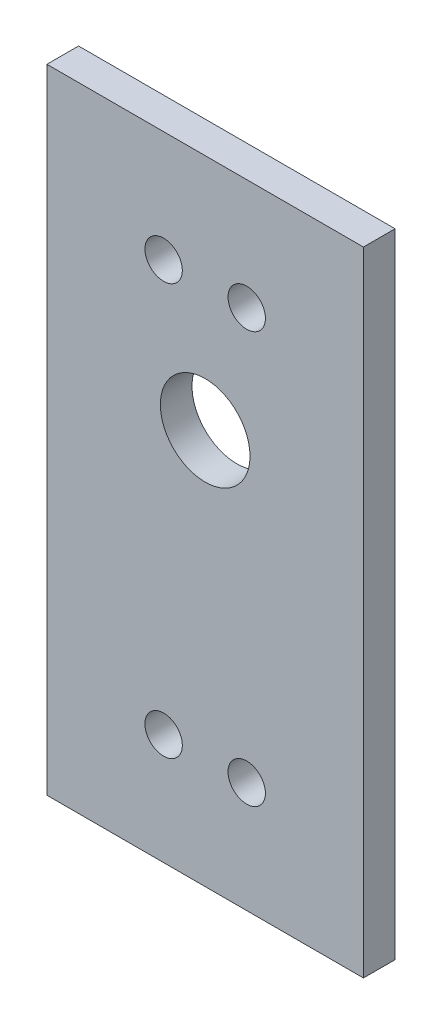
SolidWorks part; units mm, degrees
ref_plane "Front Plane" through (0, 0, 0) normal (0, 0, 1) x (1, 0, 0)
ref_plane "Top Plane" through (0, 0, 0) normal (0, 1, 0) x (1, 0, 0)
ref_plane "Right Plane" through (0, 0, 0) normal (1, 0, 0) x (0, 0, -1)
sketch "Sketch1" plane through (0, 0, 0) normal (0, 0, 1) x (1, 0, 0)
  line L1 (-19.05, 38.1) -> (19.05, 38.1)
  line L2 (-19.05, 38.1) -> (-19.05, -38.1)
  line L3 (-19.05, -38.1) -> (19.05, -38.1)
  line L4 (19.05, 38.1) -> (19.05, -38.1)
  line L5 (-19.05, 38.1) -> (19.05, -38.1) construction
  line L6 (-19.05, -38.1) -> (19.05, 38.1) construction
  point P0 (0, 0)
  dimension "D1" = 76.2
  dimension "D2" = 38.1
extrude "Boss-Extrude1" add sketch "Sketch1" along normal blind 3.81
sketch "Sketch2" plane through (0, 0, 3.81) normal (0, 0, 1) x (1, 0, 0)
  line L0 (0, 0) -> (0, -24.75) construction
  line L1 (-5, 24.75) -> (5, 24.75) construction
  line L2 (-5, 24.75) -> (-5, -24.75) construction
  line L3 (-5, -24.75) -> (5, -24.75) construction
  line L4 (5, 24.75) -> (5, -24.75) construction
  line L5 (-5, 24.75) -> (5, -24.75) construction
  line L6 (-5, -24.75) -> (5, 24.75) construction
  line L8 (-10, 20) -> (10, 20) construction
  line L9 (-10, 20) -> (-10, -20) construction
  line L10 (-10, -20) -> (10, -20) construction
  line L11 (10, 20) -> (10, -20) construction
  line L12 (-10, 20) -> (10, -20) construction
  line L13 (-10, -20) -> (10, 20) construction
  point P0 (0, 0)
  point P8 (0, -9.4592)
  dimension "D1" = 49.5
  dimension "D2" = 10
  dimension "D3" = 15.2908
  dimension "D4" = 40
  dimension "D5" = 20
hole_wizard "M4 Clearance Hole1" positions "Sketch3" profile "Sketch4" hole size "M4" standard "ANSI Metric" end condition through all
sketch "Sketch3" plane through (0, 0, 3.81) normal (0, 0, 1) x (1, 0, 0)
  point P0 (-5, 24.75)
  point P3 (5, 24.75)
  point P6 (-5, -24.75)
  point P9 (5, -24.75)
sketch "Sketch4" plane through (-5, 24.75, 3.81) normal (1, 0, 0) x (0, -1, 0)
  line L0 (0, 0) -> (0, 3.81)
  line L1 (0, 3.81) -> (2.25, 3.81)
  line L2 (2.25, 3.81) -> (2.25, 0)
  line L5 (2.25, 0) -> (0, 0)
  line L11 (0, -6.35) -> (0, 107.95) construction
  dimension "Thru Hole Dia." = 4.5
  dimension "Thru Hole Depth" = 3.81
sketch "Sketch5" plane through (0, 0, 3.81) normal (0, 0, 1) x (1, 0, 0)
  line L2 (0, 0) -> (0, -24.75) construction
  line L3 (-10, -20) -> (10, -20) construction
  circle A0 centre (0, 9.464) radius 5.3975
  dimension "D1" = 10.795
  dimension "D2" = 29.464
extrude "Cut-Extrude1" cut sketch "Sketch5" against normal up to next
